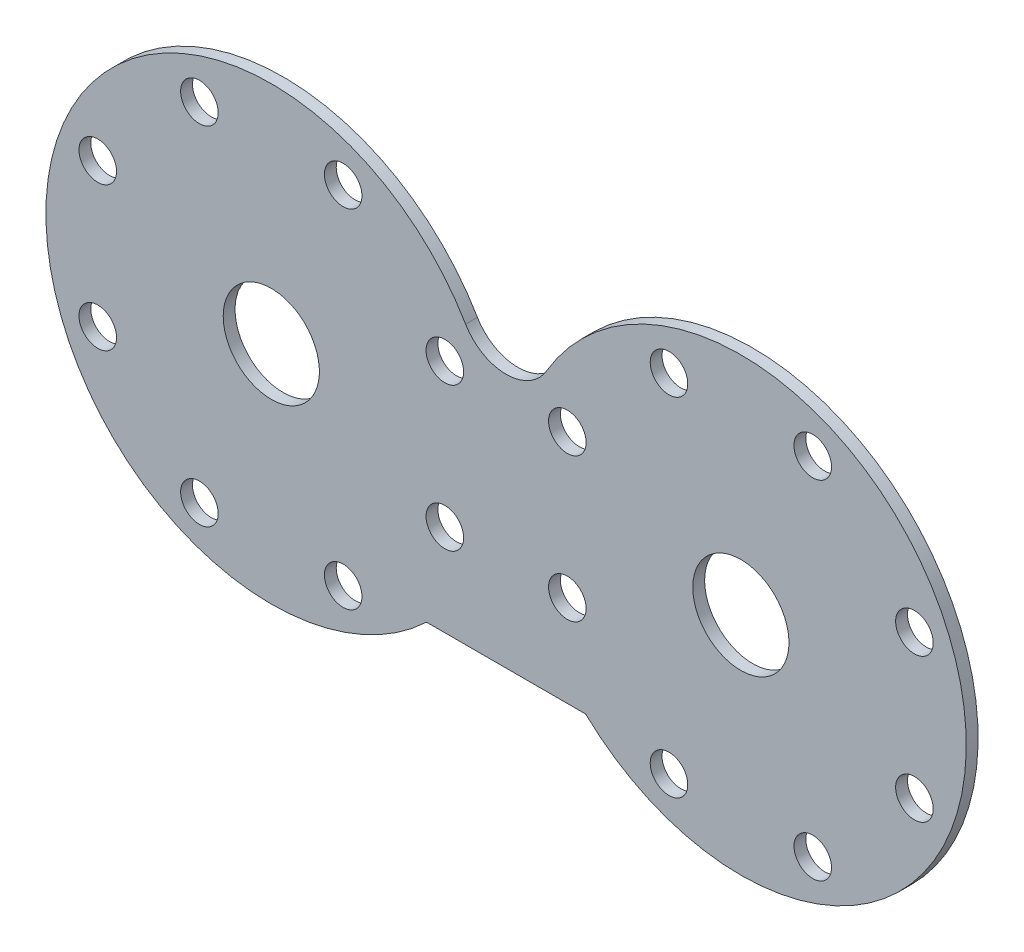
SolidWorks part; units mm, degrees
ref_plane "Front Plane" through (0, 0, 0) normal (0, 0, 1) x (1, 0, 0)
ref_plane "Top Plane" through (0, 0, 0) normal (0, 1, 0) x (1, 0, 0)
ref_plane "Right Plane" through (0, 0, 0) normal (1, 0, 0) x (0, 0, -1)
sketch "Sketch1" plane through (0, 0, 0) normal (0, 0, 1) x (1, 0, 0)
  line L0 (-15.24, -15.24) -> (46.99, -15.24) construction
  line L1 (0, -15.24) -> (29.8945, -2.8573) construction
  line L3 (15.875, -9.0824) -> (15.875, -21.3976) construction
  line L4 (31.75, -15.24) -> (20.701, -10.6634) construction
  line L5 (31.75, -15.24) -> (27.1734, -4.191) construction
  line L6 (31.75, -15.24) -> (36.3266, -4.191) construction
  line L7 (31.75, -15.24) -> (42.799, -10.6634) construction
  line L8 (31.75, -15.24) -> (42.799, -19.8166) construction
  line L9 (31.75, -15.24) -> (36.3266, -26.289) construction
  line L10 (31.75, -15.24) -> (27.1734, -26.289) construction
  line L11 (31.75, -15.24) -> (20.701, -19.8166) construction
  line L12 (10.4965, -26.289) -> (21.2535, -26.289)
  line L14 (13.1379, -7.5165) -> (0, -15.24) construction
  line L15 (0, -15.24) -> (10.4965, -26.289) construction
  line L16 (13.1379, -7.5165) -> (15.875, -5.9074) construction
  line L17 (15.875, -5.9074) -> (18.6121, -7.5165) construction
  line L18 (15.875, -5.9074) -> (13.1379, -7.5165) construction
  arc A38 (13.1379, -7.5165) -> (0, -30.48) centre (0, -15.24) ccw
  arc A39 (31.75, -30.48) -> (18.6121, -7.5165) centre (31.75, -15.24) ccw
  arc A40 (0, 0) -> (0, -30.48) centre (0, -15.24) ccw
  arc A41 (31.75, -30.48) -> (31.75, 0) centre (31.75, -15.24) ccw
  circle A42 centre (0, -15.24) radius 3.2512
  circle A43 centre (31.75, -15.24) radius 3.2512
  circle A44 centre (-11.7333, -10.3799) radius 1.27
  circle A45 centre (-4.8601, -3.5067) radius 1.27
  circle A46 centre (4.8601, -3.5067) radius 1.27
  circle A47 centre (11.7333, -10.3799) radius 1.27
  circle A48 centre (11.7333, -20.1001) radius 1.27
  circle A49 centre (4.8601, -26.9733) radius 1.27
  circle A50 centre (-4.8601, -26.9733) radius 1.27
  circle A51 centre (-11.7333, -20.1001) radius 1.27
  circle A56 centre (20.0167, -10.3799) radius 1.27
  arc A60 (13.1379, -7.5165) -> (18.6121, -7.5165) centre (15.875, -5.9074) ccw
  arc A61 (13.1379, -22.9635) -> (18.6121, -22.9635) centre (15.875, -24.5726) cw
  arc A62 (31.75, 0) -> (18.6121, -22.9635) centre (31.75, -15.24) cw
  arc A63 (13.1379, -22.9635) -> (0, 0) centre (0, -15.24) cw
  circle A64 centre (26.8899, -3.5067) radius 1.27
  circle A65 centre (36.6101, -3.5067) radius 1.27
  circle A66 centre (43.4833, -10.3799) radius 1.27
  circle A67 centre (43.4833, -20.1001) radius 1.27
  circle A68 centre (36.6101, -26.9733) radius 1.27
  circle A69 centre (26.8899, -26.9733) radius 1.27
  circle A70 centre (20.0167, -20.1001) radius 1.27
  point P10 (15.875, -21.3976)
  point P29 (0, -15.24)
  point P31 (0, 0)
  point P64 (31.75, -15.24)
  point P65 (0, 0)
  point P66 (0, 0)
  point P67 (0, 0)
  point P68 (0, 0)
  dimension "D2" = 31.75
  dimension "D4" = 6.5024
  dimension "D5" = 12.7
  dimension "D6" = 8
  dimension "D8" = 31.75
  dimension "D9" = 22.5
  dimension "D10" = 22.5
  dimension "D1" = 30.48
  dimension "D12" = 8
  dimension "D16" = 119.099
  dimension "D3" = 6.5024
  dimension "D7" = 15.24
  dimension "D11" = 12.7
  dimension "D14" = 11.049
  dimension "D13" = 3.175
  dimension "D15" = 283.081
extrude "Boss-Extrude1" add sketch "Sketch1" along normal blind 0.8
